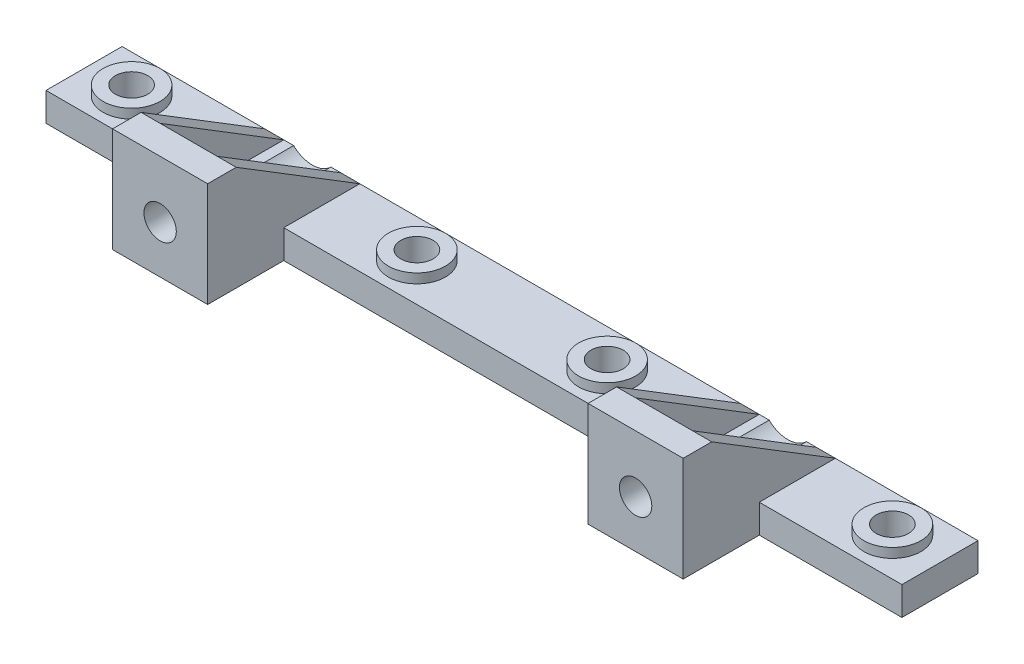
SolidWorks part; units mm, degrees
ref_plane "前视基准面" through (0, 0, 0) normal (0, 0, 1) x (1, 0, 0)
ref_plane "上视基准面" through (0, 0, 0) normal (0, 1, 0) x (1, 0, 0)
ref_plane "右视基准面" through (0, 0, 0) normal (1, 0, 0) x (0, 0, -1)
sketch "草图1" plane through (0, 0, 0) normal (0, 1, 0) x (1, 0, 0)
  line L0 (0, 0) -> (0, -25.6027) construction
  line L1 (-45, 4) -> (45, 4)
  line L2 (-45, 4) -> (-45, -4)
  line L3 (-45, -4) -> (45, -4)
  line L4 (45, 4) -> (45, -4)
  circle A0 centre (-10, 0) radius 1.7
  circle A1 centre (10, 0) radius 1.7
  circle A2 centre (40, 0) radius 1.7
  circle A3 centre (-40, 0) radius 1.7
  point P16 (0, -4)
  point P17 (45, 0)
  dimension "D1" = 3.4
  dimension "D2" = 20
  dimension "D3" = 30
  dimension "D4" = 90
  dimension "D5" = 8
extrude "凸台-拉伸1" add sketch "草图1" along normal blind 3
sketch "草图2" plane through (0, 0, 4) normal (0, 0, -1) x (-1, 0, 0)
  line L0 (-45, 3) -> (45, 3) construction
  line L1 (20, 3) -> (30, 3)
  line L2 (20, 3) -> (20, 0)
  line L3 (20, 0) -> (30, 0)
  line L4 (30, 3) -> (30, 0)
  line L5 (-45, 0) -> (45, 0) construction
  line L6 (10, 3) -> (10, 0) construction
  line L7 (41.7, 3) -> (38.3, 3) construction
  line L9 (40, 3) -> (40, 0) construction
  line L10 (11.7, 3) -> (8.3, 3) construction
  line L11 (10, 1.5) -> (40, 1.5) construction
  point P16 (25, 3)
  point P17 (25, 1.5)
  dimension "D1" = 10
extrude "凸台-拉伸2" add sketch "草图2" against normal blind 8
sketch "草图3" plane through (0, 3, 0) normal (0, 1, 0) x (1, 0, 0)
  line L0 (-20, -12) -> (-20, -4) construction
  line L1 (-30, -12) -> (-20, -12)
  line L2 (-30, -12) -> (-30, -9)
  line L3 (-30, -9) -> (-20, -9)
  line L4 (-20, -12) -> (-20, -9)
  dimension "D1" = 3
extrude "凸台-拉伸3" add sketch "草图3" along normal blind 8
sketch "草图4" plane through (0, 0, 9) normal (0, 0, -1) x (-1, 0, 0)
  line L0 (20, 3) -> (30, 3) construction
  line L1 (20, 11) -> (30, 11) construction
  circle A0 centre (25, 5) radius 1.7
  point P7 (25, 11)
  dimension "D2" = 3.4
  dimension "D1" = 2
extrude "切除-拉伸1" cut sketch "草图4" against normal through all
sketch "草图5" plane through (-20, 0, 0) normal (1, 0, 0) x (0, 0, -1)
  line L0 (-9, 11) -> (4, 3)
  line L1 (4, 3) -> (-9, 3)
  line L2 (-9, 3) -> (-9, 11)
extrude "凸台-拉伸4" add sketch "草图5" against normal blind 2
sketch "草图6" plane through (-30, 0, 0) normal (-1, 0, 0) x (0, 0, 1)
  line L0 (9, 11) -> (-4, 3)
  line L1 (-4, 3) -> (9, 3)
  line L2 (9, 3) -> (9, 11)
extrude "凸台-拉伸5" add sketch "草图6" against normal blind 2
sketch "草图7" plane through (0, 0, 9) normal (0, 0, -1) x (-1, 0, 0)
  circle A0 centre (25, 5) radius 2.8
  dimension "D1" = 5.6
extrude "切除-拉伸2" cut sketch "草图7" along normal through all
mirror "镜向1" about plane through (0, 0, 0) normal (1, 0, 0) of "切除-拉伸2", "凸台-拉伸3", "切除-拉伸1", "凸台-拉伸2", "凸台-拉伸4", "凸台-拉伸5"
sketch "草图8" plane through (0, 3, 0) normal (0, 1, 0) x (1, 0, 0)
  circle A0 centre (-40, 0) radius 3
  circle A1 centre (-10, 0) radius 3
  circle A2 centre (10, 0) radius 3
  circle A3 centre (40, 0) radius 3
  circle A4 centre (-40, 0) radius 1.7
  circle A5 centre (-10, 0) radius 1.7
  circle A6 centre (10, 0) radius 1.7
  circle A7 centre (40, 0) radius 1.7
  dimension "D1" = 6
extrude "凸台-拉伸6" add sketch "草图8" along normal blind 1
